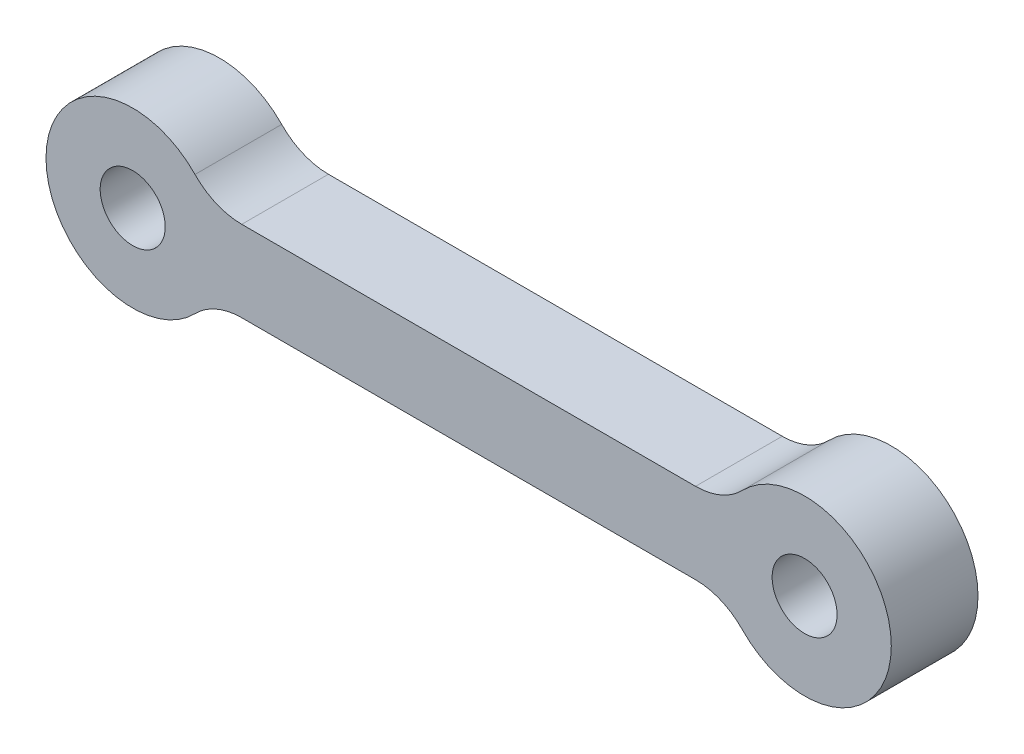
SolidWorks part; units mm, degrees
ref_plane "Front Plane" through (0, 0, 0) normal (0, 0, 1) x (1, 0, 0)
ref_plane "Top Plane" through (0, 0, 0) normal (0, 1, 0) x (1, 0, 0)
ref_plane "Right Plane" through (0, 0, 0) normal (1, 0, 0) x (0, 0, -1)
sketch "Sketch1" plane through (0, 0, 0) normal (0, 0, 1) x (1, 0, 0)
  line L0 (-15.5, 0) -> (15.5, 0) construction
  line L2 (-10.4688, 1.8669) -> (10.4688, 1.8669)
  line L4 (-10.4688, -1.8669) -> (10.4688, -1.8669)
  line L6 (-11.9624, 1.8669) -> (11.9624, -1.8669) construction
  line L7 (-11.9624, -1.8669) -> (11.9624, 1.8669) construction
  circle A0 centre (-15.5, 0) radius 1.5
  arc A1 (-12.625, 2.7811) -> (-12.625, -2.7811) centre (-15.5, 0) ccw
  circle A2 centre (15.5, 0) radius 1.5
  arc A3 (12.625, 2.7811) -> (12.625, -2.7811) centre (15.5, 0) cw
  arc A4 (10.4688, 1.8669) -> (12.625, 2.7811) centre (10.4688, 4.8669) ccw
  arc A5 (10.4688, -1.8669) -> (12.625, -2.7811) centre (10.4688, -4.8669) cw
  arc A6 (-12.625, -2.7811) -> (-10.4688, -1.8669) centre (-10.4688, -4.8669) cw
  arc A7 (-10.4688, 1.8669) -> (-12.625, 2.7811) centre (-10.4688, 4.8669) cw
  point P4 (0, 0)
  point P7 (0, 0)
  dimension "D2" = 3
  dimension "D3" = 8
  dimension "D4" = 3
  dimension "D1" = 31
extrude "Boss-Extrude1" add sketch "Sketch1" along normal blind 4
